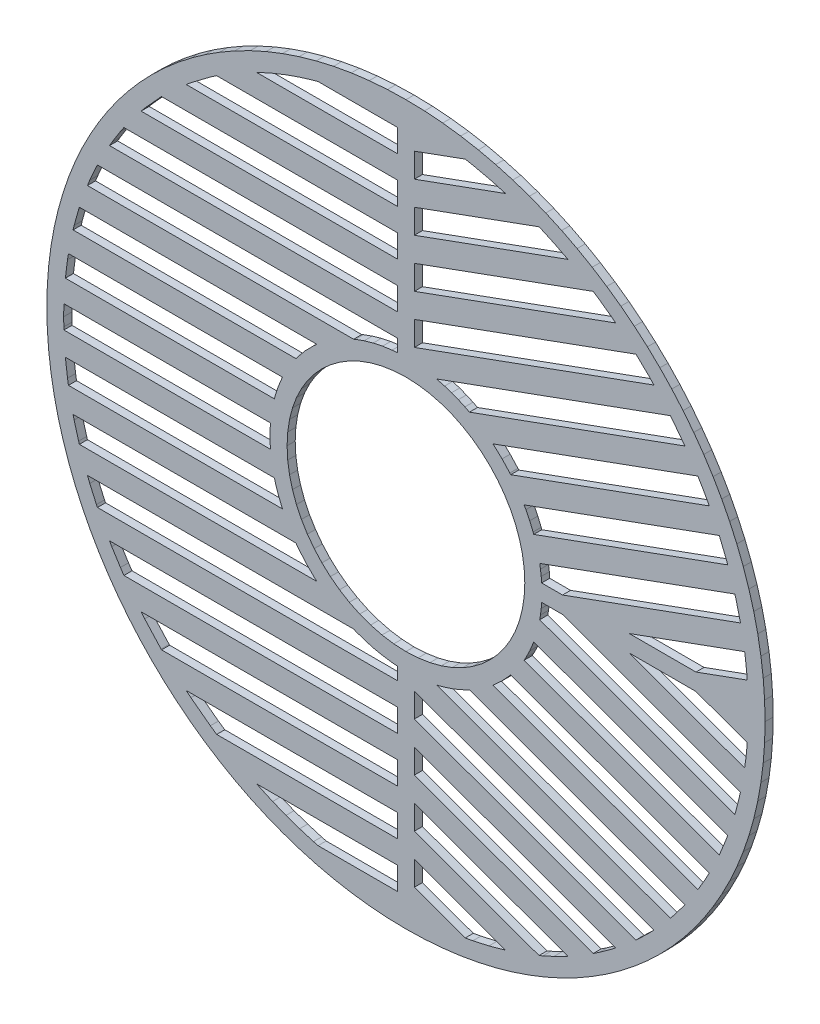
SolidWorks part; units mm, degrees
ref_plane "Front Plane" through (0, 0, 0) normal (0, 0, 1) x (1, 0, 0)
ref_plane "Top Plane" through (0, 0, 0) normal (0, 1, 0) x (1, 0, 0)
ref_plane "Right Plane" through (0, 0, 0) normal (1, 0, 0) x (0, 0, -1)
sketch "Model" plane through (0, 0, 0) normal (0, 0, 1) x (1, 0, 0)
  line L0 (87.7232, -28.4235) -> (88.8068, -28.953)
  line L1 (88.8068, -28.953) -> (93.6603, -31.1292)
  line L2 (93.6603, -31.1292) -> (98.619, -33.1056)
  line L3 (98.619, -33.1056) -> (103.6777, -34.8771)
  line L4 (103.6777, -34.8771) -> (108.8313, -36.4386)
  line L5 (108.8313, -36.4386) -> (110.5247, -36.8901)
  line L6 (110.5247, -36.8901) -> (140.0029, -36.8901)
  line L7 (140.0029, -36.8901) -> (140.0029, -28.4235)
  line L8 (140.0029, -28.4235) -> (87.7232, -28.4235)
  line L9 (146.2529, -23.3813) -> (146.2529, -32.3914)
  line L10 (146.2529, -32.3914) -> (165.1263, -39.2607)
  line L11 (165.1263, -39.2607) -> (167.9476, -38.738)
  line L12 (167.9476, -38.738) -> (173.9283, -37.4031)
  line L13 (173.9283, -37.4031) -> (179.799, -35.7911)
  line L14 (179.799, -35.7911) -> (180.0939, -35.6985)
  line L15 (180.0939, -35.6985) -> (146.2529, -23.3813)
  line L16 (61.5934, -11.4901) -> (63.3405, -12.9369)
  line L17 (63.3405, -12.9369) -> (70.5459, -18.3526)
  line L18 (70.5459, -18.3526) -> (72.9042, -19.9568)
  line L19 (72.9042, -19.9568) -> (140.0029, -19.9568)
  line L20 (140.0029, -19.9568) -> (140.0029, -11.4901)
  line L21 (140.0029, -11.4901) -> (61.5934, -11.4901)
  line L22 (146.2529, -5.3613) -> (146.2529, -14.3713)
  line L23 (146.2529, -14.3713) -> (192.5048, -31.2056)
  line L24 (192.5048, -31.2056) -> (193.9464, -30.5965)
  line L25 (193.9464, -30.5965) -> (198.0306, -28.7263)
  line L26 (198.0306, -28.7263) -> (202.0356, -26.7176)
  line L27 (202.0356, -26.7176) -> (203.2018, -26.089)
  line L28 (203.2018, -26.089) -> (146.2529, -5.3613)
  line L29 (44.8497, 5.4432) -> (46.1982, 3.8135)
  line L30 (46.1982, 3.8135) -> (52.2544, -2.8424)
  line L31 (52.2544, -2.8424) -> (52.4397, -3.0235)
  line L32 (52.4397, -3.0235) -> (140.0029, -3.0235)
  line L33 (140.0029, -3.0235) -> (140.0029, 5.4432)
  line L34 (140.0029, 5.4432) -> (44.8497, 5.4432)
  line L35 (146.2529, 12.6588) -> (146.2529, 3.6487)
  line L36 (146.2529, 3.6487) -> (212.6103, -20.5034)
  line L37 (212.6103, -20.5034) -> (214.7735, -19.061)
  line L38 (214.7735, -19.061) -> (219.5871, -15.6024)
  line L39 (219.5871, -15.6024) -> (220.968, -14.5353)
  line L40 (220.968, -14.5353) -> (146.2529, 12.6588)
  line L41 (33.1283, 22.3765) -> (33.9707, 20.9249)
  line L42 (33.9707, 20.9249) -> (37.1797, 15.8227)
  line L43 (37.1797, 15.8227) -> (38.4799, 13.9099)
  line L44 (38.4799, 13.9099) -> (140.0029, 13.9099)
  line L45 (140.0029, 13.9099) -> (140.0029, 22.3765)
  line L46 (140.0029, 22.3765) -> (33.1283, 22.3765)
  line L47 (146.2529, 30.6789) -> (146.2529, 21.6688)
  line L48 (146.2529, 21.6688) -> (228.4567, -8.2509)
  line L49 (228.4567, -8.2509) -> (228.6916, -8.0465)
  line L50 (228.6916, -8.0465) -> (232.9681, -3.9636)
  line L51 (232.9681, -3.9636) -> (235.1509, -1.6773)
  line L52 (235.1509, -1.6773) -> (146.2529, 30.6789)
  line L53 (24.9437, 39.3099) -> (25.8089, 37.1557)
  line L54 (25.8089, 37.1557) -> (28.2777, 31.599)
  line L55 (28.2777, 31.599) -> (28.6467, 30.8432)
  line L56 (28.6467, 30.8432) -> (140.0029, 30.8432)
  line L57 (140.0029, 30.8432) -> (140.0029, 35.5352)
  line L58 (140.0029, 35.5352) -> (137.97, 35.6897)
  line L59 (137.97, 35.6897) -> (134.431, 36.1762)
  line L60 (134.431, 36.1762) -> (130.9745, 36.9029)
  line L61 (130.9745, 36.9029) -> (127.6093, 37.8612)
  line L62 (127.6093, 37.8612) -> (124.3442, 39.0423)
  line L63 (124.3442, 39.0423) -> (123.7195, 39.3099)
  line L64 (123.7195, 39.3099) -> (24.9437, 39.3099)
  line L65 (166.6864, 41.2618) -> (164.9988, 40.4039)
  line L66 (164.9988, 40.4039) -> (162.5518, 39.3044)
  line L67 (162.5518, 39.3044) -> (160.0378, 38.3332)
  line L68 (160.0378, 38.3332) -> (157.461, 37.4945)
  line L69 (157.461, 37.4945) -> (154.8255, 36.7924)
  line L70 (154.8255, 36.7924) -> (154.4387, 36.7095)
  line L71 (154.4387, 36.7095) -> (241.2163, 5.1251)
  line L72 (241.2163, 5.1251) -> (242.7964, 7.0745)
  line L73 (242.7964, 7.0745) -> (246.3635, 11.8031)
  line L74 (246.3635, 11.8031) -> (246.6196, 12.1684)
  line L75 (246.6196, 12.1684) -> (166.6864, 41.2618)
  line L76 (181.9842, 53.7139) -> (181.6672, 53.3226)
  line L77 (181.6672, 53.3226) -> (178.7995, 50.2049)
  line L78 (178.7995, 50.2049) -> (175.6818, 47.3373)
  line L79 (175.6818, 47.3373) -> (175.3927, 47.103)
  line L80 (175.3927, 47.103) -> (251.4323, 19.4268)
  line L81 (251.4323, 19.4268) -> (252.8336, 21.7575)
  line L82 (252.8336, 21.7575) -> (254.3075, 24.3444)
  line L83 (254.3075, 24.3444) -> (255.68, 26.8908)
  line L84 (255.68, 26.8908) -> (181.9842, 53.7139)
  line L85 (19.6132, 56.2432) -> (20.0046, 54.6131)
  line L86 (20.0046, 54.6131) -> (21.6648, 48.6703)
  line L87 (21.6648, 48.6703) -> (21.9502, 47.7765)
  line L88 (21.9502, 47.7765) -> (110.0793, 47.7765)
  line L89 (110.0793, 47.7765) -> (108.985, 48.7388)
  line L90 (108.985, 48.7388) -> (105.7859, 51.9569)
  line L91 (105.7859, 51.9569) -> (102.885, 55.4509)
  line L92 (102.885, 55.4509) -> (102.3126, 56.2432)
  line L93 (102.3126, 56.2432) -> (19.6132, 56.2432)
  line L94 (190.536, 68.6214) -> (190.2984, 67.9532)
  line L95 (190.2984, 67.9532) -> (189.0554, 64.9761)
  line L96 (189.0554, 64.9761) -> (187.6312, 62.0989)
  line L97 (187.6312, 62.0989) -> (186.9629, 60.9118)
  line L98 (186.9629, 60.9118) -> (259.3747, 34.5561)
  line L99 (259.3747, 34.5561) -> (259.601, 35.058)
  line L100 (259.601, 35.058) -> (261.8739, 40.6217)
  line L101 (261.8739, 40.6217) -> (262.5332, 42.4165)
  line L102 (262.5332, 42.4165) -> (190.536, 68.6214)
  line L103 (16.7559, 73.1765) -> (16.7633, 73.0917)
  line L104 (16.7633, 73.0917) -> (17.5463, 66.8314)
  line L105 (17.5463, 66.8314) -> (17.8922, 64.7099)
  line L106 (17.8922, 64.7099) -> (97.3339, 64.7099)
  line L107 (97.3339, 64.7099) -> (97.0741, 65.2554)
  line L108 (97.0741, 65.2554) -> (95.7684, 68.4587)
  line L109 (95.7684, 68.4587) -> (94.6803, 71.7671)
  line L110 (94.6803, 71.7671) -> (94.306, 73.1765)
  line L111 (94.306, 73.1765) -> (16.7559, 73.1765)
  line L112 (225.9784, 82.7515) -> (268.7966, 67.1669)
  line L113 (268.7966, 67.1669) -> (269.2094, 70.2184)
  line L114 (269.2094, 70.2184) -> (269.552, 73.3195)
  line L115 (269.552, 73.3195) -> (269.7669, 75.8238)
  line L116 (269.7669, 75.8238) -> (250.7333, 82.7515)
  line L117 (250.7333, 82.7515) -> (225.9784, 82.7515)
  line L118 (193.4692, 82.7515) -> (193.3147, 80.7186)
  line L119 (193.3147, 80.7186) -> (193.0407, 78.5074)
  line L120 (193.0407, 78.5074) -> (192.7563, 76.8233)
  line L121 (192.7563, 76.8233) -> (265.1594, 50.4707)
  line L122 (265.1594, 50.4707) -> (265.6356, 52.1265)
  line L123 (265.6356, 52.1265) -> (267.11, 58.0531)
  line L124 (267.11, 58.0531) -> (267.2504, 58.7197)
  line L125 (267.2504, 58.7197) -> (201.2235, 82.7515)
  line L126 (201.2235, 82.7515) -> (193.4692, 82.7515)
  line L127 (16.2056, 90.1099) -> (16.168, 89.1034)
  line L128 (16.168, 89.1034) -> (16.1278, 85.8765)
  line L129 (16.1278, 85.8765) -> (16.168, 82.6496)
  line L130 (16.168, 82.6496) -> (16.2056, 81.6432)
  line L131 (16.2056, 81.6432) -> (92.8666, 81.6432)
  line L132 (92.8666, 81.6432) -> (92.7384, 83.4418)
  line L133 (92.7384, 83.4418) -> (92.6807, 85.8765)
  line L134 (92.6807, 85.8765) -> (92.7384, 88.3112)
  line L135 (92.7384, 88.3112) -> (92.8666, 90.1099)
  line L136 (92.8666, 90.1099) -> (16.2056, 90.1099)
  line L137 (268.7966, 104.5861) -> (225.9784, 89.0015)
  line L138 (225.9784, 89.0015) -> (250.7333, 89.0015)
  line L139 (250.7333, 89.0015) -> (269.7669, 95.9292)
  line L140 (269.7669, 95.9292) -> (269.552, 98.4335)
  line L141 (269.552, 98.4335) -> (269.2094, 101.5346)
  line L142 (269.2094, 101.5346) -> (268.7966, 104.5861)
  line L143 (17.8922, 107.0432) -> (17.5463, 104.9217)
  line L144 (17.5463, 104.9217) -> (16.7633, 98.6614)
  line L145 (16.7633, 98.6614) -> (16.7559, 98.5765)
  line L146 (16.7559, 98.5765) -> (94.306, 98.5765)
  line L147 (94.306, 98.5765) -> (94.6803, 99.986)
  line L148 (94.6803, 99.986) -> (95.7684, 103.2944)
  line L149 (95.7684, 103.2944) -> (97.0741, 106.4976)
  line L150 (97.0741, 106.4976) -> (97.3339, 107.0432)
  line L151 (97.3339, 107.0432) -> (17.8922, 107.0432)
  line L152 (265.1594, 121.2823) -> (192.7563, 94.9298)
  line L153 (192.7563, 94.9298) -> (193.0407, 93.2457)
  line L154 (193.0407, 93.2457) -> (193.3147, 91.0345)
  line L155 (193.3147, 91.0345) -> (193.4692, 89.0015)
  line L156 (193.4692, 89.0015) -> (201.2235, 89.0015)
  line L157 (201.2235, 89.0015) -> (267.2504, 113.0333)
  line L158 (267.2504, 113.0333) -> (267.11, 113.6999)
  line L159 (267.11, 113.6999) -> (265.6356, 119.6265)
  line L160 (265.6356, 119.6265) -> (265.1594, 121.2823)
  line L161 (21.9502, 123.9765) -> (21.6648, 123.0827)
  line L162 (21.6648, 123.0827) -> (20.0046, 117.1399)
  line L163 (20.0046, 117.1399) -> (19.6133, 115.5099)
  line L164 (19.6133, 115.5099) -> (102.3126, 115.5099)
  line L165 (102.3126, 115.5099) -> (102.885, 116.3021)
  line L166 (102.885, 116.3021) -> (105.7859, 119.7961)
  line L167 (105.7859, 119.7961) -> (108.985, 123.0143)
  line L168 (108.985, 123.0143) -> (110.0792, 123.9765)
  line L169 (110.0792, 123.9765) -> (21.9502, 123.9765)
  line L170 (143.1279, 129.9737) -> (138.6192, 129.7461)
  line L171 (138.6192, 129.7461) -> (134.2408, 129.0779)
  line L172 (134.2408, 129.0779) -> (130.0147, 127.9912)
  line L173 (130.0147, 127.9912) -> (125.9633, 126.5084)
  line L174 (125.9633, 126.5084) -> (122.1085, 124.6514)
  line L175 (122.1085, 124.6514) -> (118.4727, 122.4426)
  line L176 (118.4727, 122.4426) -> (115.078, 119.9041)
  line L177 (115.078, 119.9041) -> (111.9464, 117.058)
  line L178 (111.9464, 117.058) -> (109.1003, 113.9265)
  line L179 (109.1003, 113.9265) -> (106.5618, 110.5317)
  line L180 (106.5618, 110.5317) -> (104.353, 106.8959)
  line L181 (104.353, 106.8959) -> (102.496, 103.0411)
  line L182 (102.496, 103.0411) -> (101.0132, 98.9897)
  line L183 (101.0132, 98.9897) -> (99.9266, 94.7636)
  line L184 (99.9266, 94.7636) -> (99.2583, 90.3852)
  line L185 (99.2583, 90.3852) -> (99.0307, 85.8765)
  line L186 (99.0307, 85.8765) -> (99.2583, 81.3678)
  line L187 (99.2583, 81.3678) -> (99.9266, 76.9894)
  line L188 (99.9266, 76.9894) -> (101.0132, 72.7634)
  line L189 (101.0132, 72.7634) -> (102.496, 68.7119)
  line L190 (102.496, 68.7119) -> (104.353, 64.8572)
  line L191 (104.353, 64.8572) -> (106.5618, 61.2213)
  line L192 (106.5618, 61.2213) -> (109.1003, 57.8266)
  line L193 (109.1003, 57.8266) -> (111.9464, 54.6951)
  line L194 (111.9464, 54.6951) -> (115.078, 51.849)
  line L195 (115.078, 51.849) -> (118.4727, 49.3104)
  line L196 (118.4727, 49.3104) -> (122.1085, 47.1016)
  line L197 (122.1085, 47.1016) -> (125.9633, 45.2447)
  line L198 (125.9633, 45.2447) -> (130.0147, 43.7618)
  line L199 (130.0147, 43.7618) -> (134.2408, 42.6752)
  line L200 (134.2408, 42.6752) -> (138.6192, 42.007)
  line L201 (138.6192, 42.007) -> (143.1279, 41.7793)
  line L202 (143.1279, 41.7793) -> (147.6366, 42.007)
  line L203 (147.6366, 42.007) -> (152.015, 42.6752)
  line L204 (152.015, 42.6752) -> (156.2411, 43.7618)
  line L205 (156.2411, 43.7618) -> (160.2925, 45.2447)
  line L206 (160.2925, 45.2447) -> (164.1472, 47.1016)
  line L207 (164.1472, 47.1016) -> (167.7831, 49.3104)
  line L208 (167.7831, 49.3104) -> (171.1778, 51.849)
  line L209 (171.1778, 51.849) -> (174.3093, 54.6951)
  line L210 (174.3093, 54.6951) -> (177.1555, 57.8266)
  line L211 (177.1555, 57.8266) -> (179.694, 61.2213)
  line L212 (179.694, 61.2213) -> (181.9028, 64.8572)
  line L213 (181.9028, 64.8572) -> (183.7597, 68.7119)
  line L214 (183.7597, 68.7119) -> (185.2426, 72.7634)
  line L215 (185.2426, 72.7634) -> (186.3292, 76.9894)
  line L216 (186.3292, 76.9894) -> (186.9974, 81.3678)
  line L217 (186.9974, 81.3678) -> (187.2251, 85.8765)
  line L218 (187.2251, 85.8765) -> (186.9974, 90.3852)
  line L219 (186.9974, 90.3852) -> (186.3292, 94.7636)
  line L220 (186.3292, 94.7636) -> (185.2426, 98.9897)
  line L221 (185.2426, 98.9897) -> (183.7597, 103.0411)
  line L222 (183.7597, 103.0411) -> (181.9028, 106.8959)
  line L223 (181.9028, 106.8959) -> (179.694, 110.5317)
  line L224 (179.694, 110.5317) -> (177.1555, 113.9265)
  line L225 (177.1555, 113.9265) -> (174.3093, 117.058)
  line L226 (174.3093, 117.058) -> (171.1778, 119.9041)
  line L227 (171.1778, 119.9041) -> (167.7831, 122.4426)
  line L228 (167.7831, 122.4426) -> (164.1472, 124.6514)
  line L229 (164.1472, 124.6514) -> (160.2925, 126.5084)
  line L230 (160.2925, 126.5084) -> (156.2411, 127.9912)
  line L231 (156.2411, 127.9912) -> (152.015, 129.0779)
  line L232 (152.015, 129.0779) -> (147.6366, 129.7461)
  line L233 (147.6366, 129.7461) -> (143.1279, 129.9737)
  line L234 (259.3747, 137.1969) -> (186.9629, 110.8412)
  line L235 (186.9629, 110.8412) -> (187.6312, 109.6541)
  line L236 (187.6312, 109.6541) -> (189.0554, 106.777)
  line L237 (189.0554, 106.777) -> (190.2984, 103.7998)
  line L238 (190.2984, 103.7998) -> (190.536, 103.1317)
  line L239 (190.536, 103.1317) -> (262.5332, 129.3365)
  line L240 (262.5332, 129.3365) -> (261.8739, 131.1313)
  line L241 (261.8739, 131.1313) -> (259.601, 136.695)
  line L242 (259.601, 136.695) -> (259.3747, 137.1969)
  line L243 (28.6467, 140.9099) -> (28.2777, 140.1541)
  line L244 (28.2777, 140.1541) -> (25.8089, 134.5974)
  line L245 (25.8089, 134.5974) -> (24.9437, 132.4432)
  line L246 (24.9437, 132.4432) -> (123.7195, 132.4432)
  line L247 (123.7195, 132.4432) -> (124.3442, 132.7108)
  line L248 (124.3442, 132.7108) -> (127.6093, 133.8918)
  line L249 (127.6093, 133.8918) -> (130.9745, 134.8501)
  line L250 (130.9745, 134.8501) -> (134.431, 135.5769)
  line L251 (134.431, 135.5769) -> (137.97, 136.0633)
  line L252 (137.97, 136.0633) -> (140.0029, 136.2179)
  line L253 (140.0029, 136.2179) -> (140.0029, 140.9099)
  line L254 (140.0029, 140.9099) -> (28.6467, 140.9099)
  line L255 (251.4323, 152.3262) -> (175.3927, 124.6501)
  line L256 (175.3927, 124.6501) -> (175.6818, 124.4158)
  line L257 (175.6818, 124.4158) -> (178.7995, 121.5481)
  line L258 (178.7995, 121.5481) -> (181.6672, 118.4304)
  line L259 (181.6672, 118.4304) -> (181.9842, 118.0391)
  line L260 (181.9842, 118.0391) -> (255.68, 144.8622)
  line L261 (255.68, 144.8622) -> (254.3075, 147.4086)
  line L262 (254.3075, 147.4086) -> (252.8336, 149.9955)
  line L263 (252.8336, 149.9955) -> (251.4323, 152.3262)
  line L264 (38.4799, 157.8432) -> (37.1797, 155.9303)
  line L265 (37.1797, 155.9303) -> (33.9707, 150.8282)
  line L266 (33.9707, 150.8282) -> (33.1284, 149.3765)
  line L267 (33.1284, 149.3765) -> (140.0029, 149.3765)
  line L268 (140.0029, 149.3765) -> (140.0029, 157.8432)
  line L269 (140.0029, 157.8432) -> (38.4799, 157.8432)
  line L270 (241.2163, 166.628) -> (154.4387, 135.0435)
  line L271 (154.4387, 135.0435) -> (154.8255, 134.9606)
  line L272 (154.8255, 134.9606) -> (157.461, 134.2585)
  line L273 (157.461, 134.2585) -> (160.0378, 133.4198)
  line L274 (160.0378, 133.4198) -> (162.5518, 132.4486)
  line L275 (162.5518, 132.4486) -> (164.9988, 131.3491)
  line L276 (164.9988, 131.3491) -> (166.6864, 130.4913)
  line L277 (166.6864, 130.4913) -> (246.6196, 159.5846)
  line L278 (246.6196, 159.5846) -> (246.3635, 159.95)
  line L279 (246.3635, 159.95) -> (242.7964, 164.6786)
  line L280 (242.7964, 164.6786) -> (241.2163, 166.628)
  line L281 (52.4397, 174.7765) -> (52.2544, 174.5955)
  line L282 (52.2544, 174.5955) -> (46.1982, 167.9396)
  line L283 (46.1982, 167.9396) -> (44.8497, 166.3099)
  line L284 (44.8497, 166.3099) -> (140.0029, 166.3099)
  line L285 (140.0029, 166.3099) -> (140.0029, 174.7765)
  line L286 (140.0029, 174.7765) -> (52.4397, 174.7765)
  line L287 (228.4567, 180.0039) -> (146.2529, 150.0842)
  line L288 (146.2529, 150.0842) -> (146.2529, 141.0742)
  line L289 (146.2529, 141.0742) -> (235.1509, 173.4304)
  line L290 (235.1509, 173.4304) -> (232.9681, 175.7167)
  line L291 (232.9681, 175.7167) -> (228.6916, 179.7995)
  line L292 (228.6916, 179.7995) -> (228.4567, 180.0039)
  line L293 (72.9042, 191.7099) -> (70.5459, 190.1056)
  line L294 (70.5459, 190.1056) -> (63.3405, 184.69)
  line L295 (63.3405, 184.69) -> (61.5934, 183.2432)
  line L296 (61.5934, 183.2432) -> (140.0029, 183.2432)
  line L297 (140.0029, 183.2432) -> (140.0029, 191.7099)
  line L298 (140.0029, 191.7099) -> (72.9042, 191.7099)
  line L299 (212.6103, 192.2564) -> (146.2529, 168.1043)
  line L300 (146.2529, 168.1043) -> (146.2529, 159.0942)
  line L301 (146.2529, 159.0942) -> (220.968, 186.2883)
  line L302 (220.968, 186.2883) -> (219.5871, 187.3555)
  line L303 (219.5871, 187.3555) -> (214.7735, 190.8141)
  line L304 (214.7735, 190.8141) -> (212.6103, 192.2564)
  line L305 (192.5048, 202.9587) -> (146.2529, 186.1244)
  line L306 (146.2529, 186.1244) -> (146.2529, 177.1143)
  line L307 (146.2529, 177.1143) -> (203.2018, 197.842)
  line L308 (203.2018, 197.842) -> (202.0356, 198.4707)
  line L309 (202.0356, 198.4707) -> (198.0306, 200.4794)
  line L310 (198.0306, 200.4794) -> (193.9464, 202.3496)
  line L311 (193.9464, 202.3496) -> (192.5048, 202.9587)
  line L312 (110.5247, 208.6432) -> (108.8313, 208.1916)
  line L313 (108.8313, 208.1916) -> (103.6777, 206.6301)
  line L314 (103.6777, 206.6301) -> (98.619, 204.8586)
  line L315 (98.619, 204.8586) -> (93.6603, 202.8822)
  line L316 (93.6603, 202.8822) -> (88.8068, 200.706)
  line L317 (88.8068, 200.706) -> (87.7232, 200.1765)
  line L318 (87.7232, 200.1765) -> (140.0029, 200.1765)
  line L319 (140.0029, 200.1765) -> (140.0029, 208.6432)
  line L320 (140.0029, 208.6432) -> (110.5247, 208.6432)
  line L321 (165.1263, 211.0138) -> (146.2529, 204.1444)
  line L322 (146.2529, 204.1444) -> (146.2529, 195.1344)
  line L323 (146.2529, 195.1344) -> (180.0939, 207.4515)
  line L324 (180.0939, 207.4515) -> (179.799, 207.5441)
  line L325 (179.799, 207.5441) -> (173.9283, 209.1561)
  line L326 (173.9283, 209.1561) -> (167.9476, 210.491)
  line L327 (167.9476, 210.491) -> (165.1263, 211.0138)
  line L328 (143.1279, 219.1266) -> (149.9849, 218.9532)
  line L329 (149.9849, 218.9532) -> (156.7519, 218.4387)
  line L330 (156.7519, 218.4387) -> (163.4206, 217.5913)
  line L331 (163.4206, 217.5913) -> (169.9824, 216.4195)
  line L332 (169.9824, 216.4195) -> (176.4292, 214.9316)
  line L333 (176.4292, 214.9316) -> (182.7524, 213.136)
  line L334 (182.7524, 213.136) -> (188.9437, 211.0411)
  line L335 (188.9437, 211.0411) -> (194.9948, 208.6552)
  line L336 (194.9948, 208.6552) -> (200.8973, 205.9867)
  line L337 (200.8973, 205.9867) -> (206.6428, 203.0441)
  line L338 (206.6428, 203.0441) -> (212.2229, 199.8356)
  line L339 (212.2229, 199.8356) -> (217.6293, 196.3696)
  line L340 (217.6293, 196.3696) -> (222.8536, 192.6546)
  line L341 (222.8536, 192.6546) -> (227.8873, 188.6988)
  line L342 (227.8873, 188.6988) -> (232.7223, 184.5107)
  line L343 (232.7223, 184.5107) -> (237.3499, 180.0986)
  line L344 (237.3499, 180.0986) -> (241.762, 175.4709)
  line L345 (241.762, 175.4709) -> (245.9501, 170.636)
  line L346 (245.9501, 170.636) -> (249.9059, 165.6022)
  line L347 (249.9059, 165.6022) -> (253.621, 160.3779)
  line L348 (253.621, 160.3779) -> (257.0869, 154.9716)
  line L349 (257.0869, 154.9716) -> (260.2954, 149.3914)
  line L350 (260.2954, 149.3914) -> (263.2381, 143.646)
  line L351 (263.2381, 143.646) -> (265.9066, 137.7435)
  line L352 (265.9066, 137.7435) -> (268.2924, 131.6924)
  line L353 (268.2924, 131.6924) -> (270.3874, 125.501)
  line L354 (270.3874, 125.501) -> (272.1829, 119.1778)
  line L355 (272.1829, 119.1778) -> (273.6708, 112.7311)
  line L356 (273.6708, 112.7311) -> (274.8427, 106.1692)
  line L357 (274.8427, 106.1692) -> (275.69, 99.5006)
  line L358 (275.69, 99.5006) -> (276.2046, 92.7336)
  line L359 (276.2046, 92.7336) -> (276.378, 85.8765)
  line L360 (276.378, 85.8765) -> (276.2046, 79.0195)
  line L361 (276.2046, 79.0195) -> (275.69, 72.2525)
  line L362 (275.69, 72.2525) -> (274.8427, 65.5838)
  line L363 (274.8427, 65.5838) -> (273.6708, 59.022)
  line L364 (273.6708, 59.022) -> (272.1829, 52.5752)
  line L365 (272.1829, 52.5752) -> (270.3874, 46.252)
  line L366 (270.3874, 46.252) -> (268.2924, 40.0607)
  line L367 (268.2924, 40.0607) -> (265.9066, 34.0096)
  line L368 (265.9066, 34.0096) -> (263.2381, 28.1071)
  line L369 (263.2381, 28.1071) -> (260.2954, 22.3616)
  line L370 (260.2954, 22.3616) -> (257.0869, 16.7815)
  line L371 (257.0869, 16.7815) -> (253.621, 11.3751)
  line L372 (253.621, 11.3751) -> (249.9059, 6.1509)
  line L373 (249.9059, 6.1509) -> (245.9501, 1.1171)
  line L374 (245.9501, 1.1171) -> (241.762, -3.7178)
  line L375 (241.762, -3.7178) -> (237.3499, -8.3455)
  line L376 (237.3499, -8.3455) -> (232.7223, -12.7576)
  line L377 (232.7223, -12.7576) -> (227.8873, -16.9457)
  line L378 (227.8873, -16.9457) -> (222.8536, -20.9015)
  line L379 (222.8536, -20.9015) -> (217.6293, -24.6166)
  line L380 (217.6293, -24.6166) -> (212.2229, -28.0825)
  line L381 (212.2229, -28.0825) -> (206.6428, -31.291)
  line L382 (206.6428, -31.291) -> (200.8973, -34.2337)
  line L383 (200.8973, -34.2337) -> (194.9948, -36.9021)
  line L384 (194.9948, -36.9021) -> (188.9437, -39.288)
  line L385 (188.9437, -39.288) -> (182.7524, -41.3829)
  line L386 (182.7524, -41.3829) -> (176.4292, -43.1785)
  line L387 (176.4292, -43.1785) -> (169.9824, -44.6664)
  line L388 (169.9824, -44.6664) -> (163.4206, -45.8382)
  line L389 (163.4206, -45.8382) -> (156.7519, -46.6856)
  line L390 (156.7519, -46.6856) -> (149.9849, -47.2002)
  line L391 (149.9849, -47.2002) -> (143.1279, -47.3736)
  line L392 (143.1279, -47.3736) -> (136.2709, -47.2002)
  line L393 (136.2709, -47.2002) -> (129.5038, -46.6856)
  line L394 (129.5038, -46.6856) -> (122.8352, -45.8382)
  line L395 (122.8352, -45.8382) -> (116.2733, -44.6664)
  line L396 (116.2733, -44.6664) -> (109.8266, -43.1785)
  line L397 (109.8266, -43.1785) -> (103.5034, -41.3829)
  line L398 (103.5034, -41.3829) -> (97.312, -39.288)
  line L399 (97.312, -39.288) -> (91.2609, -36.9021)
  line L400 (91.2609, -36.9021) -> (85.3585, -34.2337)
  line L401 (85.3585, -34.2337) -> (79.613, -31.291)
  line L402 (79.613, -31.291) -> (74.0329, -28.0825)
  line L403 (74.0329, -28.0825) -> (68.6265, -24.6166)
  line L404 (68.6265, -24.6166) -> (63.4022, -20.9015)
  line L405 (63.4022, -20.9015) -> (58.3684, -16.9457)
  line L406 (58.3684, -16.9457) -> (53.5335, -12.7576)
  line L407 (53.5335, -12.7576) -> (48.9058, -8.3455)
  line L408 (48.9058, -8.3455) -> (44.4937, -3.7178)
  line L409 (44.4937, -3.7178) -> (40.3056, 1.1171)
  line L410 (40.3056, 1.1171) -> (36.3499, 6.1509)
  line L411 (36.3499, 6.1509) -> (32.6348, 11.3751)
  line L412 (32.6348, 11.3751) -> (29.1688, 16.7815)
  line L413 (29.1688, 16.7815) -> (25.9603, 22.3616)
  line L414 (25.9603, 22.3616) -> (23.0177, 28.1071)
  line L415 (23.0177, 28.1071) -> (20.3492, 34.0096)
  line L416 (20.3492, 34.0096) -> (17.9634, 40.0607)
  line L417 (17.9634, 40.0607) -> (15.8684, 46.252)
  line L418 (15.8684, 46.252) -> (14.0728, 52.5752)
  line L419 (14.0728, 52.5752) -> (12.5849, 59.022)
  line L420 (12.5849, 59.022) -> (11.4131, 65.5838)
  line L421 (11.4131, 65.5838) -> (10.5657, 72.2525)
  line L422 (10.5657, 72.2525) -> (10.0512, 79.0195)
  line L423 (10.0512, 79.0195) -> (9.8778, 85.8765)
  line L424 (9.8778, 85.8765) -> (10.0512, 92.7336)
  line L425 (10.0512, 92.7336) -> (10.5657, 99.5006)
  line L426 (10.5657, 99.5006) -> (11.4131, 106.1692)
  line L427 (11.4131, 106.1692) -> (12.5849, 112.7311)
  line L428 (12.5849, 112.7311) -> (14.0728, 119.1778)
  line L429 (14.0728, 119.1778) -> (15.8684, 125.501)
  line L430 (15.8684, 125.501) -> (17.9634, 131.6924)
  line L431 (17.9634, 131.6924) -> (20.3492, 137.7435)
  line L432 (20.3492, 137.7435) -> (23.0177, 143.646)
  line L433 (23.0177, 143.646) -> (25.9603, 149.3914)
  line L434 (25.9603, 149.3914) -> (29.1688, 154.9716)
  line L435 (29.1688, 154.9716) -> (32.6348, 160.3779)
  line L436 (32.6348, 160.3779) -> (36.3499, 165.6022)
  line L437 (36.3499, 165.6022) -> (40.3056, 170.636)
  line L438 (40.3056, 170.636) -> (44.4937, 175.4709)
  line L439 (44.4937, 175.4709) -> (48.9058, 180.0986)
  line L440 (48.9058, 180.0986) -> (53.5335, 184.5107)
  line L441 (53.5335, 184.5107) -> (58.3684, 188.6988)
  line L442 (58.3684, 188.6988) -> (63.4022, 192.6546)
  line L443 (63.4022, 192.6546) -> (68.6265, 196.3696)
  line L444 (68.6265, 196.3696) -> (74.0329, 199.8356)
  line L445 (74.0329, 199.8356) -> (79.613, 203.0441)
  line L446 (79.613, 203.0441) -> (85.3585, 205.9867)
  line L447 (85.3585, 205.9867) -> (91.2609, 208.6552)
  line L448 (91.2609, 208.6552) -> (97.312, 211.0411)
  line L449 (97.312, 211.0411) -> (103.5034, 213.136)
  line L450 (103.5034, 213.136) -> (109.8266, 214.9316)
  line L451 (109.8266, 214.9316) -> (116.2733, 216.4195)
  line L452 (116.2733, 216.4195) -> (122.8352, 217.5913)
  line L453 (122.8352, 217.5913) -> (129.5038, 218.4387)
  line L454 (129.5038, 218.4387) -> (136.2709, 218.9532)
  line L455 (136.2709, 218.9532) -> (143.1279, 219.1266)
extrude "Boss-Extrude1" add sketch "Model" along normal blind 3
